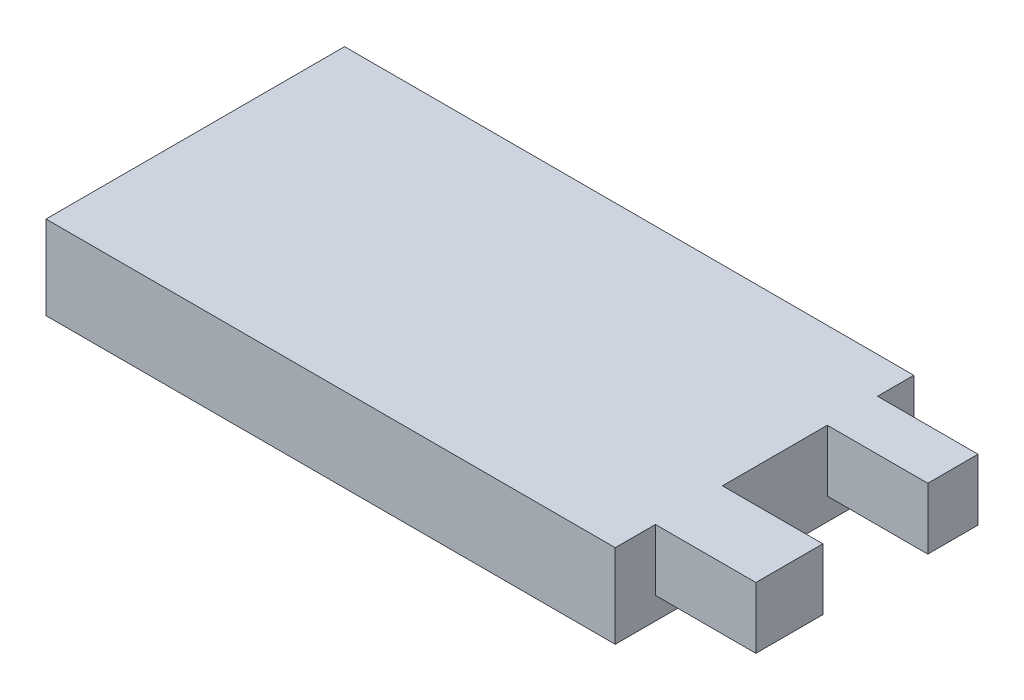
SolidWorks part; units mm, degrees
ref_plane "Alzado" through (0, 0, 0) normal (0, 0, 1) x (1, 0, 0)
ref_plane "Planta" through (0, 0, 0) normal (0, 1, 0) x (1, 0, 0)
ref_plane "Vista lateral" through (0, 0, 0) normal (1, 0, 0) x (0, 0, -1)
sketch "Croquis1" plane through (0, 0, 0) normal (0, 1, 0) x (1, 0, 0)
  line L1 (51, -26.75) -> (-51, -26.75)
  line L2 (51, -26.75) -> (51, 26.75)
  line L3 (51, 26.75) -> (-51, 26.75)
  line L4 (-51, -26.75) -> (-51, 26.75)
  line L5 (51, -26.75) -> (-51, 26.75) construction
  line L6 (51, 26.75) -> (-51, -26.75) construction
  point P0 (0, 0)
  dimension "D1" = 102
  dimension "D2" = 53.5
extrude "Saliente-Extruir1" add sketch "Croquis1" along normal blind 15
sketch "Croquis2" plane through (51, 0, 0) normal (1, 0, 0) x (0, 0, -1)
  line L0 (-26.75, 15) -> (26.75, 15) construction
  line L1 (-19.55, 15) -> (-7.55, 15)
  line L2 (-19.55, 15) -> (-19.55, 4)
  line L3 (-19.55, 4) -> (-7.55, 4)
  line L4 (-7.55, 15) -> (-7.55, 4)
  line L5 (-26.75, 4) -> (26.75, 4) construction
  line L6 (11.25, 15) -> (20.25, 15)
  line L7 (11.25, 15) -> (11.25, 4)
  line L8 (11.25, 4) -> (20.25, 4)
  line L9 (20.25, 15) -> (20.25, 4)
  line L10 (-26.75, 15) -> (-26.75, 0) construction
  line L11 (26.75, 15) -> (26.75, 0) construction
  line L12 (-26.75, 0) -> (26.75, 0) construction
  dimension "D1" = 4
  dimension "D2" = 12
  dimension "D3" = 9
  dimension "D4" = 6.5
  dimension "D5" = 19.2
extrude "Saliente-Extruir2" add sketch "Croquis2" along normal blind 18
